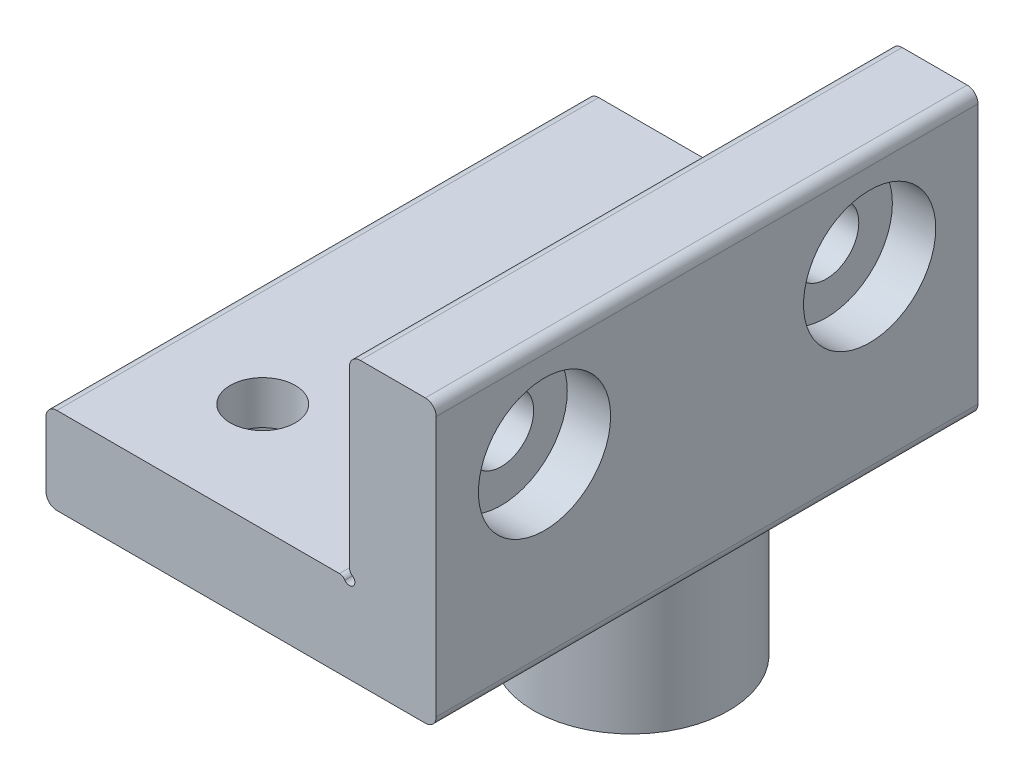
SolidWorks part; units mm, degrees
ref_plane "Front Plane" through (0, 0, 0) normal (0, 0, 1) x (1, 0, 0)
ref_plane "Top Plane" through (0, 0, 0) normal (0, 1, 0) x (1, 0, 0)
ref_plane "Right Plane" through (0, 0, 0) normal (1, 0, 0) x (0, 0, -1)
sketch "Sketch1" plane through (0, 0, 0) normal (0, 0, 1) x (1, 0, 0)
  line L0 (0, 0) -> (-14, 0)
  line L1 (-14, 0) -> (-14, -4)
  line L2 (-14, -4) -> (4, -4)
  line L3 (4, -4) -> (4, 9)
  line L4 (4, 9) -> (0, 9)
  line L5 (0, 9) -> (0, 0)
  point P6 (2.5, 6.5)
  dimension "D1" = 9
  dimension "D2" = 14
  dimension "D3" = 4
extrude "Boss-Extrude1" add sketch "Sketch1" along normal blind 25
sketch "Sketch2" plane through (0, -4, 0) normal (0, -1, 0) x (1, 0, 0)
  line L0 (-14, 25) -> (4, 25) construction
  line L5 (-14, 25) -> (-14, 0) construction
  circle A0 centre (-9, 20) radius 1.5
  point P2 (0, 0)
  point P5 (-9, 21.7724)
  point P7 (0, 0)
  point P8 (0, 0)
  point P9 (-6.2093, 20)
  point P13 (0, 0)
  dimension "D2" = 3
  dimension "D1" = 5
  dimension "D3" = 5
extrude "Cut-Extrude1" cut sketch "Sketch2" against normal up to next
sketch "Sketch3" plane through (4, 0, 0) normal (1, 0, 0) x (0, 0, -1)
  line L0 (0, -4) -> (0, 9) construction
  line L1 (0, 9) -> (0, 0) construction
  line L2 (0, 9) -> (0, 0) construction
  line L3 (-25, -4) -> (-25, 9) construction
  circle A0 centre (-5, 4.5) radius 1.5
  circle A1 centre (-20, 4.5) radius 1.5
  point P7 (0, 4.5)
  point P11 (-20, 5.8708)
  point P12 (0, 0)
  dimension "D1" = 3
  dimension "D2" = 5
  dimension "D3" = 5
extrude "Cut-Extrude2" cut sketch "Sketch3" against normal up to next
sketch "Sketch5" plane through (0, 0, 25) normal (0, 0, 1) x (1, 0, 0)
  circle A0 centre (0, 0) radius 0.25
  dimension "D1" = 0.5
extrude "Cut-Extrude3" cut sketch "Sketch5" against normal up to next
fillet "Fillet1" radius 0.3 2 edges at (0, 0.25, 12.5) (-0.25, 0, 12.5)
sketch "Sketch6" plane through (4, 0, 0) normal (1, 0, 0) x (0, 0, -1)
  circle A0 centre (-20, 4.5) radius 3.05
  circle A1 centre (-5, 4.5) radius 3.05
  dimension "D1" = 6.1
extrude "Cut-Extrude4" cut sketch "Sketch6" against normal blind 2
sketch "Sketch7" plane through (0, -4, 0) normal (0, -1, 0) x (1, 0, 0)
  circle A0 centre (-9, 20) radius 3.05
  dimension "D1" = 6.1
extrude "Cut-Extrude5" cut sketch "Sketch7" against normal blind 2
sketch "Sketch9" plane through (0, -4, 0) normal (0, -1, 0) x (1, 0, 0)
  line L0 (-14, 0) -> (4, 0) construction
  circle A0 centre (-5, 7) radius 4.5
  point P4 (-5, 0)
  dimension "D2" = 9
  dimension "D1" = 7
extrude "Boss-Extrude2" add sketch "Sketch9" along normal blind 10.5
sketch "Sketch10" plane through (0, -14.5, 0) normal (0, -1, 0) x (1, 0, 0)
  circle A0 centre (-5, 7) radius 0.75
  dimension "D1" = 1.5
extrude "Cut-Extrude6" cut sketch "Sketch10" against normal blind 10.5
fillet "Fillet2" radius 0.5 5 edges at (4, 9, 12.5) (0, 9, 12.5) (-14, 0, 12.5) (-14, -4, 12.5) (4, -4, 12.5)
